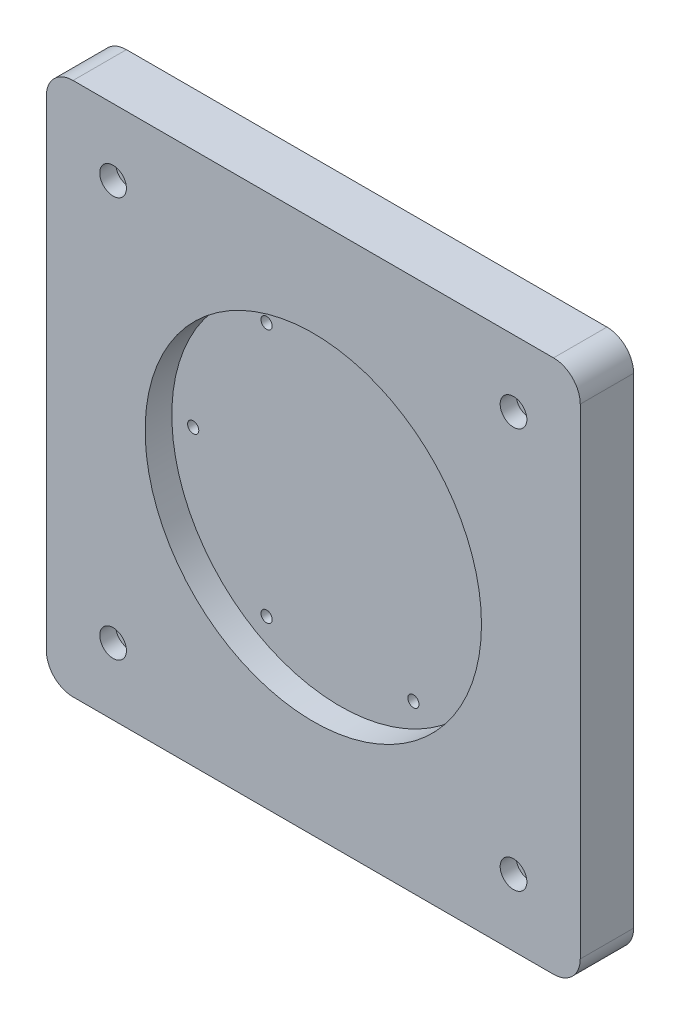
SolidWorks part; units mm, degrees
material "6063-O"
ref_plane "正面" through (0, 0, 0) normal (0, 0, 1) x (1, 0, 0)
ref_plane "平面" through (0, 0, 0) normal (0, 1, 0) x (1, 0, 0)
ref_plane "右側面" through (0, 0, 0) normal (1, 0, 0) x (0, 0, -1)
sketch "ｽｹｯﾁ1" plane through (0, 0, 0) normal (0, 0, 1) x (1, 0, 0)
  line L1 (-100, 100) -> (100, 100)
  line L2 (-100, 100) -> (-100, -100)
  line L3 (-100, -100) -> (100, -100)
  line L4 (100, 100) -> (100, -100)
  line L5 (-100, 100) -> (100, -100) construction
  line L6 (-100, -100) -> (100, 100) construction
  circle A0 centre (0, 0) radius 63
  point P0 (0, 0)
  dimension "D1" = 126
  dimension "D2" = 200
  dimension "D3" = 200
extrude "ﾎﾞｽ - 押し出し1" add sketch "ｽｹｯﾁ1" along normal blind 10
sketch "ｽｹｯﾁ2" plane through (0, 0, 0) normal (0, 0, -1) x (-1, 0, 0)
  line L4 (-100, 100) -> (-100, -100)
  line L5 (-100, -100) -> (100, -100)
  line L6 (100, -100) -> (100, 100)
  line L7 (100, 100) -> (-100, 100)
  line L8 (-100, 100) -> (-100, -100)
  line L9 (-100, -100) -> (100, -100)
  line L10 (100, -100) -> (100, 100)
  line L11 (100, 100) -> (-100, 100)
  dimension "D1" = 0
extrude "ﾎﾞｽ - 押し出し2" add sketch "ｽｹｯﾁ2" along normal blind 10
sketch "ｽｹｯﾁ3" plane through (0, 0, 0) normal (0, 0, 1) x (1, 0, 0)
  line L0 (0, 0) -> (0, -63) construction
  line L1 (0, 0) -> (27.5, -47.6314) construction
  circle A0 centre (27.5, -47.6314) radius 2.1
  circle A1 centre (-27.5, -47.6314) radius 2.1
  circle A2 centre (-55, 0) radius 2.1
  circle A3 centre (-27.5, 47.6314) radius 2.1
  circle A4 centre (27.5, 47.6314) radius 2.1
  circle A5 centre (55, 0) radius 2.1
  circle A6 centre (0, 0) radius 63 construction
  point P15 (0, 0)
  dimension "D1" = 55
  dimension "D2" = 4.2
  dimension "D4" = 30
  dimension "D3" = 6
extrude "ｶｯﾄ - 押し出し1" cut sketch "ｽｹｯﾁ3" against normal blind 10
sketch "ｽｹｯﾁ4" plane through (0, 0, 10) normal (0, 0, 1) x (1, 0, 0)
  line L0 (100, 100) -> (-100, 100) construction
  line L1 (100, -100) -> (100, 100) construction
  circle A0 centre (75, 75) radius 2.75
  circle A1 centre (75, -75) radius 2.75
  circle A2 centre (-75, -75) radius 2.75
  circle A3 centre (-75, 75) radius 2.75
  point P15 (0, 0)
  dimension "D1" = 5.5
  dimension "D2" = 25
  dimension "D3" = 25
  dimension "D4" = 4
extrude "ｶｯﾄ - 押し出し2" cut sketch "ｽｹｯﾁ4" against normal through all
sketch "ｽｹｯﾁ5" plane through (0, 0, 10) normal (0, 0, 1) x (1, 0, 0)
  circle A0 centre (75, -75) radius 5
  circle A1 centre (-75, -75) radius 5
  circle A2 centre (-75, 75) radius 5
  circle A3 centre (75, 75) radius 5
  point P12 (0, 0)
  dimension "D1" = 10
  dimension "D2" = 4
extrude "ｶｯﾄ - 押し出し3" cut sketch "ｽｹｯﾁ5" against normal blind 6
fillet "ﾌｨﾚｯﾄ1" radius 10 4 edges at (-100, -100, 0) (100, -100, 0) (100, 100, 0) (-100, 100, 0)
